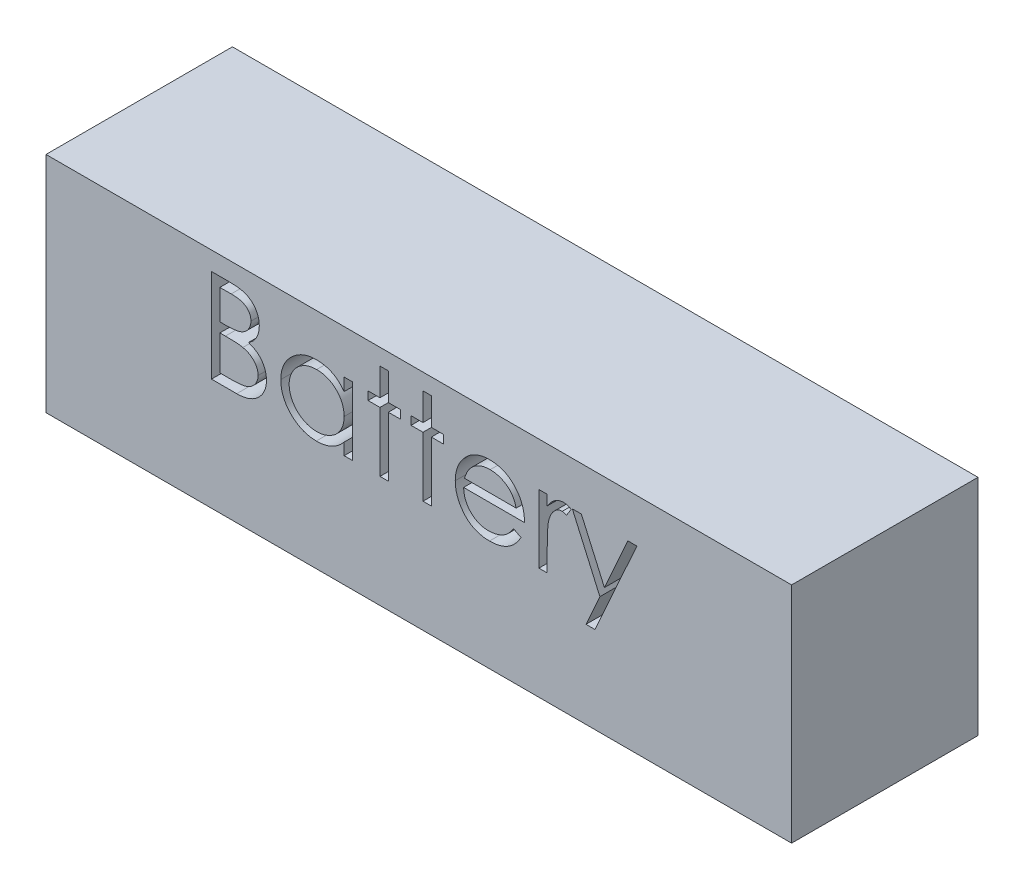
SolidWorks part; units mm, degrees
ref_plane "Front Plane" through (0, 0, 0) normal (0, 0, 1) x (1, 0, 0)
ref_plane "Top Plane" through (0, 0, 0) normal (0, 1, 0) x (1, 0, 0)
ref_plane "Right Plane" through (0, 0, 0) normal (1, 0, 0) x (0, 0, -1)
sketch "Sketch1" plane through (0, 0, 0) normal (0, 0, 1) x (1, 0, 0)
  line L1 (-46.8534, 48.6024) -> (54.7466, 48.6024)
  line L2 (-46.8534, 48.6024) -> (-46.8534, 18.1224)
  line L3 (-46.8534, 18.1224) -> (54.7466, 18.1224)
  line L4 (54.7466, 48.6024) -> (54.7466, 18.1224)
  dimension "D1" = 101.6
  dimension "D2" = 30.48
extrude "Boss-Extrude1" add sketch "Sketch1" along normal blind 25.4
sketch "Sketch2" plane through (0, 0, 25.4) normal (0, 0, 1) x (1, 0, 0)
  line L0 (-46.8534, 33.3624) -> (54.7466, 33.3624) construction
  line L1 (-46.8534, 48.6024) -> (-46.8534, 18.1224) construction
  line L2 (54.7466, 18.1224) -> (54.7466, 48.6024) construction
  text T0 "Battery" font "Century Gothic" height in points 48
extrude "Cut-Extrude1" cut sketch "Sketch2" against normal through all
